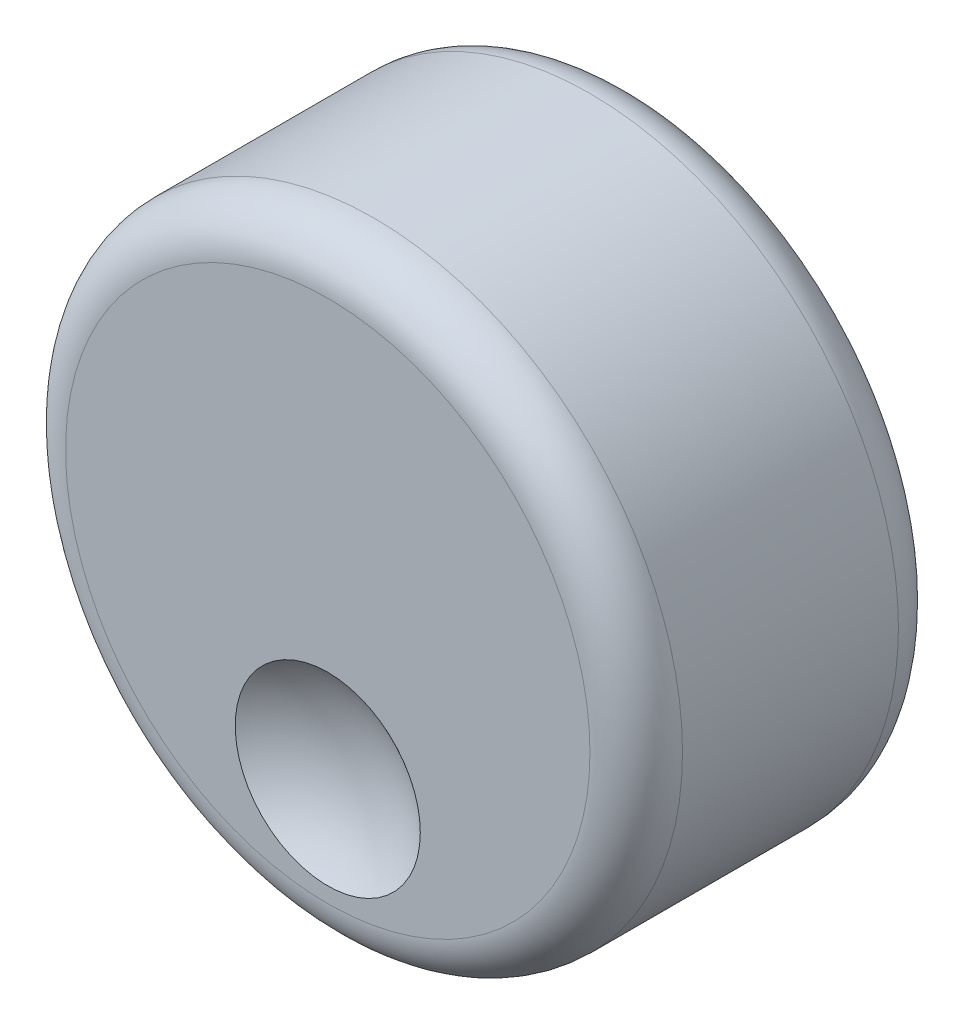
SolidWorks part; units mm, degrees
material "ABS"
ref_plane "Front Plane" through (0, 0, 0) normal (0, 0, 1) x (1, 0, 0)
ref_plane "Top Plane" through (0, 0, 0) normal (0, 1, 0) x (1, 0, 0)
ref_plane "Right Plane" through (0, 0, 0) normal (1, 0, 0) x (0, 0, -1)
sketch "Sketch1" plane through (0, 0, 0) normal (0, 0, 1) x (1, 0, 0)
  circle A0 centre (0, 0) radius 10
  dimension "D1" = 20
extrude "Boss-Extrude1" add sketch "Sketch1" along normal blind 10
fillet "Fillet1" radius 1.5 2 edges at (10, 0, 0) (10, 0, 10)
sketch "Sketch2" plane through (0, 0, 0) normal (0, 0, -1) x (-1, 0, 0)
  circle A0 centre (0, 0) radius 3
  dimension "D1" = 6
extrude "Cut-Extrude1" cut sketch "Sketch2" against normal blind 8
chamfer "Chamfer1" distance 1 angle 45 1 edges at (-3, 0, 0)
sketch "Sketch3" plane through (0, 0, 0) normal (1, 0, 0) x (0, 0, -1)
  line L0 (-8.5, -10) -> (-1.5, -10) construction
  line L1 (-10, 8.5) -> (-10, -8.5) construction
  line L2 (-19, -5) -> (-9, -5) construction
  line L3 (-19, -5) -> (-9, -5)
  arc A0 (-19, -5) -> (-9, -5) centre (-14, -5) ccw
  dimension "D1" = 10
  dimension "D2" = 5
  dimension "D3" = 4
revolve "Cut-Revolve2" cut sketch "Sketch3" angle 360 about L2
